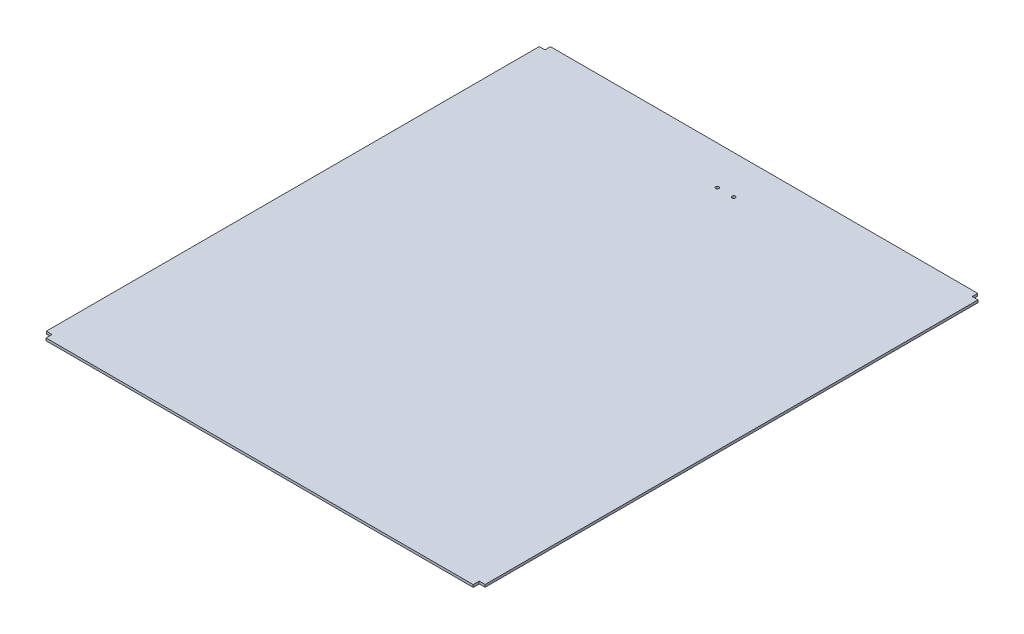
SolidWorks part; units mm, degrees
ref_plane "Front Plane" through (0, 0, 0) normal (0, 0, 1) x (1, 0, 0)
ref_plane "Top Plane" through (0, 0, 0) normal (0, 1, 0) x (1, 0, 0)
ref_plane "Right Plane" through (0, 0, 0) normal (1, 0, 0) x (0, 0, -1)
sketch "Sketch1" plane through (0, 0, 0) normal (0, 1, 0) x (1, 0, 0)
  line L1 (0.0465, 0.2911) -> (534.0465, 0.2911)
  line L2 (0.0465, 0.2911) -> (0.0465, 600.2911)
  line L3 (0.0465, 600.2911) -> (534.0465, 600.2911)
  line L4 (534.0465, 0.2911) -> (534.0465, 600.2911)
extrude "Boss-Extrude1" add sketch "Sketch1" along normal blind 3
ref_plane "Plane1" through (534.0465, 3, -600.2911) normal (0, 0, -1) x (-1, 0, 0)
sketch "Sketch3" plane through (0, 0, 0) normal (0, 1, 0) x (1, 0, 0)
  line L1 (7, 607) -> (527, 607)
  line L2 (7, 607) -> (7, -7)
  line L3 (7, -7) -> (527, -7)
  line L4 (527, 607) -> (527, -7)
extrude "Boss-Extrude2" add sketch "Sketch3" along normal blind 3
sketch "Sketch4" plane through (0, 3, 0) normal (0, 1, 0) x (1, 0, 0)
  circle A0 centre (257.025, 560) radius 2
  circle A1 centre (277.025, 560) radius 2
extrude "Cut-Extrude2" cut sketch "Sketch4" against normal blind 10
